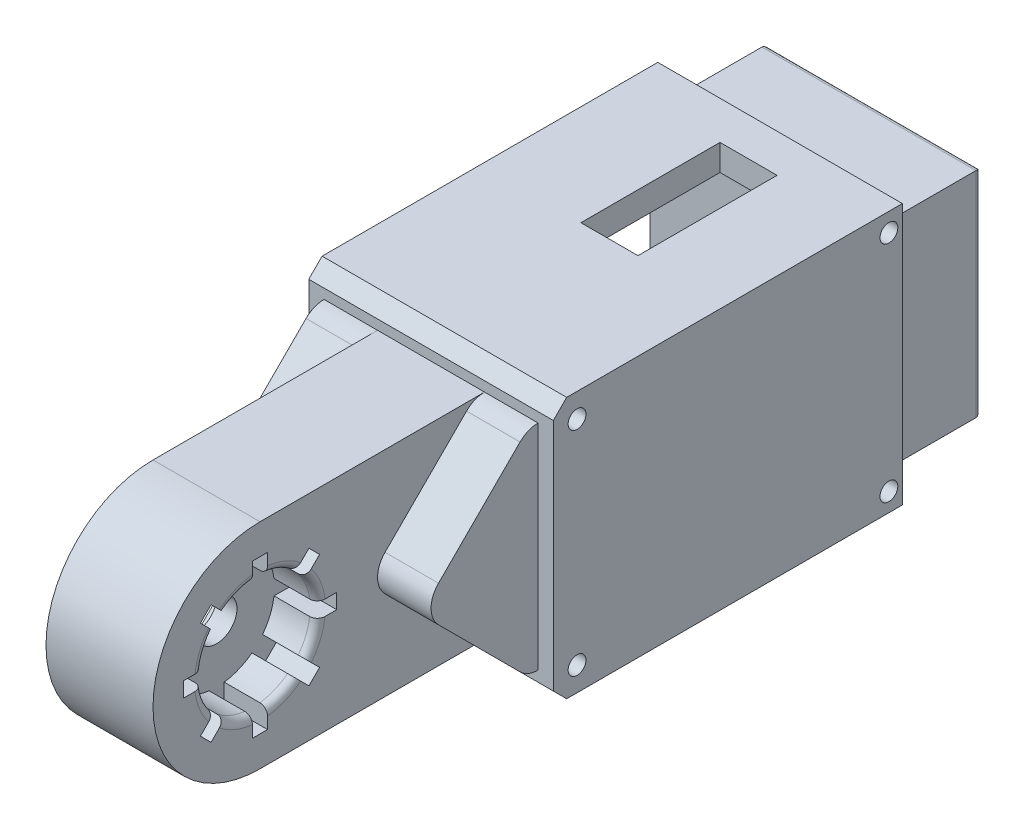
SolidWorks part; units mm, degrees
ref_plane "Front Plane" through (0, 0, 0) normal (0, 0, 1) x (1, 0, 0)
ref_plane "Top Plane" through (0, 0, 0) normal (0, 1, 0) x (1, 0, 0)
ref_plane "Right Plane" through (0, 0, 0) normal (1, 0, 0) x (0, 0, -1)
sketch "Sketch2" plane through (0, 0, 0) normal (0, 0, 1) x (1, 0, 0)
  line L1 (-21, 21) -> (21, 21)
  line L2 (-21, 21) -> (-21, -21)
  line L3 (-21, -21) -> (21, -21)
  line L4 (21, 21) -> (21, -21)
  line L5 (-21, 21) -> (21, -21) construction
  line L6 (-21, -21) -> (21, 21) construction
  point P0 (0, 0)
  dimension "D1" = 42
  dimension "D2" = 42
extrude "Boss-Extrude1" add sketch "Sketch2" along normal blind 89
ref_plane "Plane1" through (0, 0, 89) normal (0, 0, 1) x (1, 0, 0)
sketch "Sketch3" plane through (0, 0, 89) normal (0, 0, 1) x (1, 0, 0)
  line L0 (21, 21) -> (-21, 21) construction
  line L1 (10.5, -21) -> (-10.5, -21)
  line L2 (10.5, -21) -> (10.5, 21)
  line L3 (10.5, 21) -> (-10.5, 21)
  line L4 (-10.5, -21) -> (-10.5, 21)
  line L5 (10.5, -21) -> (-10.5, 21) construction
  line L6 (10.5, 21) -> (-10.5, -21) construction
  point P0 (0, 0)
  dimension "D1" = 21
ref_plane "Plane4" through (0, 0, 0) normal (0, 0, -1) x (-1, 0, 0)
extrude "Boss-Extrude2" add sketch "Sketch3" along normal blind 42
ref_plane "Plane5" through (-10.5, 0, 0) normal (-1, 0, 0) x (0, 0, 1)
sketch "Sketch8" plane through (-10.5, 0, 0) normal (-1, 0, 0) x (0, 0, 1)
  line L0 (131, 21) -> (131, -21) construction
  line L1 (131, 21) -> (131, -21)
  arc A0 (131, 21) -> (131, -21) centre (131, 0) cw
  dimension "D1" = 21
extrude "Boss-Extrude3" add sketch "Sketch8" against normal blind 21
ref_plane "Plane6" through (-10.5, 0, 0) normal (-1, 0, 0) x (0, 0, 1)
sketch "Sketch9" plane through (-10.5, 0, 0) normal (-1, 0, 0) x (0, 0, 1)
  line L0 (89, 21) -> (89, -21) construction
  line L1 (131, 21) -> (131, -21)
  circle A0 centre (131, 0) radius 11.35
  dimension "D1" = 42
  dimension "D2" = 22.7
extrude "Cut-Extrude2" cut sketch "Sketch9" against normal blind 8.5 contours A0
ref_plane "Plane7" through (10.5, 0, 0) normal (1, 0, 0) x (0, 0, -1)
sketch "Sketch11" plane through (10.5, 0, 0) normal (1, 0, 0) x (0, 0, -1)
  line L0 (-131, 21) -> (-131, -21)
  circle A0 centre (-131, 0) radius 11.35
  dimension "D1" = 22.7
extrude "Cut-Extrude3" cut sketch "Sketch11" against normal blind 8.5 contours A0
ref_plane "Plane8" through (-2, 0, 0) normal (-1, 0, 0) x (0, 0, 1)
sketch "Sketch12" plane through (-2, 0, 0) normal (-1, 0, 0) x (0, 0, 1)
  circle A0 centre (131, 0) radius 3.975
  dimension "D1" = 7.95
extrude "Cut-Extrude4" cut sketch "Sketch12" against normal through all
ref_plane "Plane10" through (-2, 0, 0) normal (-1, 0, 0) x (0, 0, 1)
ref_plane "Plane11" through (-10.5, 0, 0) normal (-1, 0, 0) x (0, 0, 1)
sketch "Sketch20" plane through (-10.5, 0, 0) normal (-1, 0, 0) x (0, 0, 1)
  line L0 (131, 0) -> (110, 0)
  line L1 (110, 0) -> (110, 21)
  line L2 (110, 0) -> (110, -21)
  line L4 (110, 21) -> (89, 21)
  line L6 (110, -21) -> (89, -21)
  line L7 (89, 21) -> (110, 0)
  line L8 (89, -21) -> (110, 0)
  line L9 (89, 21) -> (89, -21)
  circle A0 centre (131, 0) radius 11.35
  dimension "D1" = 21
extrude "Boss-Extrude4" add sketch "Sketch20" along normal blind 10.5 and the other way blind 31.5 contours L7 L9 L8
fillet "Fillet1" radius 5 1 edges at (15.75, 0, 110)
fillet "Fillet2" radius 5 1 edges at (-15.75, 0, 110)
fillet "Fillet3" radius 5 1 edges at (-15.75, -21, 89)
fillet "Fillet4" radius 5 1 edges at (-15.75, 21, 89)
fillet "Fillet5" radius 5 1 edges at (15.75, -21, 89)
fillet "Fillet6" radius 5 1 edges at (15.75, 21, 89)
fillet "Fillet7" radius 1.5 1 edges at (-10.5, 0, 142.35)
fillet "Fillet8" radius 1.5 1 edges at (10.5, 0, 119.65)
sketch "Sketch21" plane through (-10.5, 0, 0) normal (-1, 0, 0) x (0, 0, 1)
  line L1 (129.5207, 10.6415) -> (132.4793, 10.6415)
  line L2 (129.5207, 10.6415) -> (129.5207, 15.0585)
  line L3 (129.5207, 15.0585) -> (132.4793, 15.0585)
  line L4 (132.4793, 10.6415) -> (132.4793, 15.0585)
  line L5 (129.5207, 10.6415) -> (132.4793, 15.0585) construction
  line L6 (129.5207, 15.0585) -> (132.4793, 10.6415) construction
  circle A0 centre (131, 0) radius 12.85 construction
  point P0 (131, 12.85)
  dimension "D1" = 4.417
extrude "Cut-Extrude5" cut sketch "Sketch21" against normal blind 8.5
pattern_circular "CirPattern2" count 8 over 360 about axis through (0, 0, 131) along (1, 0, 0) of "Cut-Extrude5"
ref_plane "Plane12" through (0, 21, 0) normal (0, 1, 0) x (1, 0, 0)
ref_plane "Plane13" through (10.5, 0, 0) normal (1, 0, 0) x (0, 0, -1)
ref_plane "Plane14" through (0, 0, 0) normal (1, 0, 0) x (0, 0, -1)
mirror "Mirror1" about plane through (0, 0, 0) normal (1, 0, 0) of "CirPattern2", "Cut-Extrude5"
ref_plane "Plane15" through (21, 0, 0) normal (1, 0, 0) x (0, 0, -1)
sketch "Sketch24" plane through (21, 0, 0) normal (1, 0, 0) x (0, 0, -1)
  line L1 (-86.9289, 21) -> (0, 21)
  line L2 (-86.9289, 21) -> (-86.9289, 25.5452)
  line L3 (-86.9289, 25.5452) -> (0, 25.5452)
  line L4 (0, 21) -> (0, 25.5452)
  line L5 (-86.9289, -21) -> (0, -21)
  line L6 (-86.9289, -21) -> (-86.9289, -25.6891)
  line L7 (-86.9289, -25.6891) -> (0, -25.6891)
  line L8 (0, -21) -> (0, -25.6891)
extrude "Boss-Extrude6" add sketch "Sketch24" against normal blind 42
sketch "Sketch25" plane through (21, 0, 0) normal (1, 0, 0) x (0, 0, -1)
  line L0 (-18.4289, -25.6891) -> (-18.4289, 25.5452)
  line L1 (-86.9289, 25.5452) -> (-18.4289, 25.5452)
  line L2 (-86.9289, 25.5452) -> (-86.9289, -25.6891)
  line L3 (-86.9289, -25.6891) -> (-18.4289, -25.6891)
  dimension "D1" = 68.5
extrude "Boss-Extrude7" add sketch "Sketch25" along normal blind 3
ref_plane "Plane18" through (0, 0, 0) normal (0, 0, -1) x (-1, 0, 0)
ref_plane "Plane19" through (-21, 0, 0) normal (-1, 0, 0) x (0, 0, 1)
sketch "Sketch28" plane through (-21, 0, 0) normal (-1, 0, 0) x (0, 0, 1)
  line L0 (86.9289, -25.6891) -> (0, -25.6891) construction
  line L1 (86.9289, 25.5452) -> (18.4289, 25.5452)
  line L2 (86.9289, 25.5452) -> (86.9289, -25.6891)
  line L3 (86.9289, -25.6891) -> (18.4289, -25.6891)
  line L4 (18.4289, 25.5452) -> (18.4289, -25.6891)
  dimension "D1" = 68.5
extrude "Boss-Extrude8" add sketch "Sketch28" along normal blind 3
ref_plane "Plane20" through (-24, 0, 0) normal (-1, 0, 0) x (0, 0, 1)
sketch "Sketch30" plane through (-24, 0, 0) normal (-1, 0, 0) x (0, 0, 1)
  line L1 (81.9289, 20.4302) -> (19.9289, 20.4302)
  line L2 (81.9289, 20.4302) -> (81.9289, -20.5741)
  line L3 (81.9289, -20.5741) -> (19.9289, -20.5741)
  line L4 (19.9289, 20.4302) -> (19.9289, -20.5741)
  line L5 (81.9289, 20.4302) -> (19.9289, -20.5741) construction
  line L6 (81.9289, -20.5741) -> (19.9289, 20.4302) construction
  line L8 (86.9289, 25.5452) -> (18.4289, 25.5452) construction
  line L9 (18.4289, -25.6891) -> (86.9289, -25.6891) construction
  line L10 (86.9289, -21) -> (86.9289, 21) construction
  point P0 (50.9289, -0.0719)
  dimension "D1" = 5.115
  dimension "D2" = 5.115
  dimension "D3" = 62
  dimension "D4" = 5
extrude "Cut-Extrude6" cut sketch "Sketch30" against normal blind 45
ref_plane "Plane21" through (21, 0, 0) normal (1, 0, 0) x (0, 0, -1)
sketch "Sketch31" plane through (21, 0, 0) normal (1, 0, 0) x (0, 0, -1)
  line L0 (0, -25.6891) -> (0, 25.5452) construction
  line L1 (-18.4289, -25.6891) -> (0, -25.6891)
  line L2 (-18.4289, -25.6891) -> (-18.4289, -21.0741)
  line L3 (-18.4289, -21.0741) -> (0, -21.0741)
  line L4 (0, -25.6891) -> (0, -21.0741)
  line L6 (-18.4289, 25.5452) -> (0, 25.5452)
  line L7 (-18.4289, 25.5452) -> (-18.4289, 20.9302)
  line L8 (-18.4289, 20.9302) -> (0, 20.9302)
  line L9 (0, 25.5452) -> (0, 20.9302)
  dimension "D1" = 4.615
  dimension "D2" = 4.615
extrude "Cut-Extrude7" cut sketch "Sketch31" against normal through all
chamfer "Chamfer1" distance 1.5 angle 45 4 edges at (0, 20.9302, 18.4289) (21, -0.0719, 18.4289) (0, -21.0741, 18.4289) (-21, -0.0719, 18.4289)
ref_plane "Plane22" through (0, 0, 0) normal (0, 0, -1) x (-1, 0, 0)
sketch "Sketch32" plane through (0, 0, 0) normal (0, 0, -1) x (-1, 0, 0)
  line L1 (15, 15) -> (-15, 15)
  line L2 (15, 15) -> (15, -15)
  line L3 (15, -15) -> (-15, -15)
  line L4 (-15, 15) -> (-15, -15)
  line L5 (15, 15) -> (-15, -15) construction
  line L6 (15, -15) -> (-15, 15) construction
  point P0 (0, 0)
  dimension "D1" = 30
  dimension "D2" = 30
extrude "Cut-Extrude8" cut sketch "Sketch32" against normal blind 16.8
ref_plane "Plane23" through (0, 0, 19.9289) normal (0, 0, 1) x (1, 0, 0)
sketch "Sketch33" plane through (0, 0, 19.9289) normal (0, 0, 1) x (1, 0, 0)
  circle A0 centre (0, 0) radius 5
  dimension "D1" = 10
extrude "Cut-Extrude9" cut sketch "Sketch33" against normal blind 16.8
ref_plane "Plane24" through (-21, 0, 0) normal (-1, 0, 0) x (0, 0, 1)
sketch "Sketch34" plane through (-24, 0, 0) normal (-1, 0, 0) x (0, 0, 1)
  line L0 (86.9289, -0.0719) -> (103.6427, -0.0719) construction
  line L2 (88.3304, -21.6696) -> (88.3304, -28.2221)
  line L3 (88.3304, -28.2221) -> (81.7779, -28.2221)
  line L4 (81.7779, -28.2221) -> (88.3304, -21.6696)
  line L5 (86.9289, -25.6891) -> (86.9289, 25.5452) construction
  line L6 (88.3304, 28.0782) -> (81.7779, 28.0782)
  line L7 (88.3304, 21.5257) -> (88.3304, 28.0782)
  line L8 (81.7779, 28.0782) -> (88.3304, 21.5257)
extrude "Cut-Extrude10" cut sketch "Sketch34" against normal through all
chamfer "Chamfer2" distance 6 angle 45 1 edges at (-1.5, 20.4302, 81.9289)
chamfer "Chamfer3" distance 6 angle 45 1 edges at (-1.5, -20.5741, 81.9289)
chamfer "Chamfer4" distance 6 angle 45 1 edges at (-1.5, 20.4302, 19.9289)
chamfer "Chamfer5" distance 6 angle 45 1 edges at (-1.5, -20.5741, 19.9289)
sketch "Sketch35" plane through (-24, 0, 0) normal (-1, 0, 0) x (0, 0, 1)
  line L0 (78.9289, -17.5741) -> (85.6199, -24.3801) construction
  line L1 (82.2744, 20.8332) -> (85.6199, 24.2362) construction
  line L2 (81.9289, -14.5741) -> (75.9289, -20.5741) construction
  line L3 (84.3109, -25.6891) -> (86.9289, -23.0711) construction
  line L4 (78.9289, 17.4302) -> (85.6199, 24.2362) construction
  line L5 (75.9289, 20.4302) -> (81.9289, 14.4302) construction
  line L6 (86.9289, 22.9272) -> (84.3109, 25.5452) construction
  line L7 (18.4289, 25.5452) -> (21.0741, 21.9048) construction
  line L9 (18.4289, -25.6891) -> (21.074, -22.0485) construction
  line L10 (18.4289, 25.5452) -> (18.4289, -25.6891) construction
  circle A0 centre (21.0741, 21.9048) radius 1.75
  circle A1 centre (82.2744, 20.8332) radius 1.75
  circle A2 centre (82.2744, -20.9771) radius 1.75
  circle A3 centre (21.074, -22.0485) radius 1.75
  dimension "D5" = 3.5
  dimension "D1" = 36.003
  dimension "D2" = 36
  dimension "D3" = 4.5
  dimension "D4" = 4.5
extrude "Cut-Extrude11" cut sketch "Sketch35" against normal through all
ref_plane "Plane26" through (0, -25.6891, 0) normal (0, -1, 0) x (-1, 0, 0)
sketch "Sketch38" plane through (0, -25.6891, 0) normal (0, -1, 0) x (-1, 0, 0)
  line L0 (-24, -18.4289) -> (24, -18.4289) construction
  line L1 (4.2922, -53.2289) -> (-6.9078, -53.2289)
  line L2 (4.2922, -53.2289) -> (4.2922, -25.9289)
  line L3 (4.2922, -25.9289) -> (-6.9078, -25.9289)
  line L4 (-6.9078, -53.2289) -> (-6.9078, -25.9289)
  dimension "D1" = 7.5
  dimension "D2" = 27.3
  dimension "D3" = 11.2
extrude "Cut-Extrude12" cut sketch "Sketch38" against normal through all
fillet "Fillet9" radius 1 4 edges at (21, -0.0719, 0) (0, 20.9302, 0) (0, -21.0741, 0) (-21, -0.0719, 0)
fillet "Fillet10" radius 1 4 edges at (0, 15, 0) (15, 0, 0) (0, -15, 0) (-15, 0, 0)
